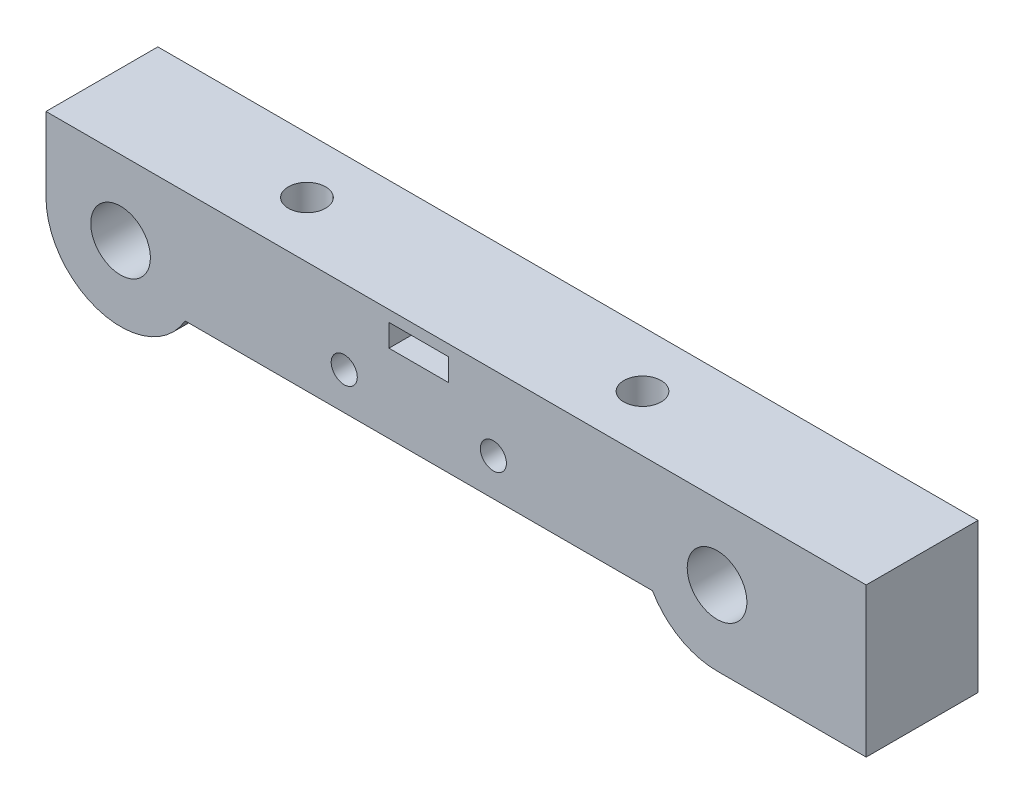
SolidWorks part; units mm, degrees
material "ABS"
ref_plane "Plano frontal" through (0, 0, 0) normal (0, 0, 1) x (1, 0, 0)
ref_plane "Plano superior" through (0, 0, 0) normal (0, 1, 0) x (1, 0, 0)
ref_plane "Plano direito" through (0, 0, 0) normal (1, 0, 0) x (0, 0, -1)
sketch "Esboço1" plane through (0, 0, 0) normal (0, 0, 1) x (1, 0, 0)
  line L0 (0, 0) -> (0, -15) construction
  line L2 (-50, -10) -> (-50, 0)
  line L3 (-50, 0) -> (50, 0)
  line L4 (10, -10) -> (-10, -10) construction
  line L5 (4, -1.5) -> (-4, -1.5)
  line L6 (4, -1.5) -> (4, -4.5)
  line L7 (-31.3397, -15) -> (31.3397, -15)
  line L8 (4, -4.5) -> (-4, -4.5)
  line L9 (-4, -1.5) -> (-4, -4.5)
  line L10 (4, -1.5) -> (-4, -4.5) construction
  line L11 (4, -4.5) -> (-4, -1.5) construction
  line L12 (50, 0) -> (60, 0)
  line L13 (60, 0) -> (60, -20)
  line L14 (60, -20) -> (40, -20)
  circle A0 centre (-40, -10) radius 4
  circle A1 centre (40, -10) radius 4
  arc A2 (-50, -10) -> (-31.3397, -15) centre (-40, -10) ccw
  arc A3 (40, -20) -> (31.3397, -15) centre (40, -10) cw
  circle A4 centre (10, -10) radius 1.75
  circle A5 centre (-10, -10) radius 1.75
  point P0 (0, 0)
  point P2 (0, -3)
  point P13 (63, -13)
  point P24 (0, -10)
  dimension "D3" = 8
  dimension "D4" = 80
  dimension "D2" = 10
  dimension "D8" = 3.5
  dimension "D1" = 100
  dimension "D5" = 3
  dimension "D6" = 8
  dimension "D7" = 3
  dimension "D9" = 20
  dimension "D10" = 15
  dimension "D11" = 5
  dimension "D12" = 10
extrude "Ressalto-extrusão1" add sketch "Esboço1" along normal blind 15
sketch "Esboço2" plane through (0, -15, 0) normal (0, -1, 0) x (1, 0, 0)
  line L0 (0, 0) -> (0, 15) construction
  line L1 (-31.3397, 0) -> (31.3397, 0) construction
  line L2 (-31.3397, 15) -> (31.3397, 15) construction
  circle A0 centre (-22.5, 7.5) radius 2.5
  circle A1 centre (22.5, 7.5) radius 2.5
  point P11 (0, 7.5)
  dimension "D2" = 5
  dimension "D1" = 45
extrude "Corte-extrusão1" cut sketch "Esboço2" against normal blind 15 contours A1 | A0
